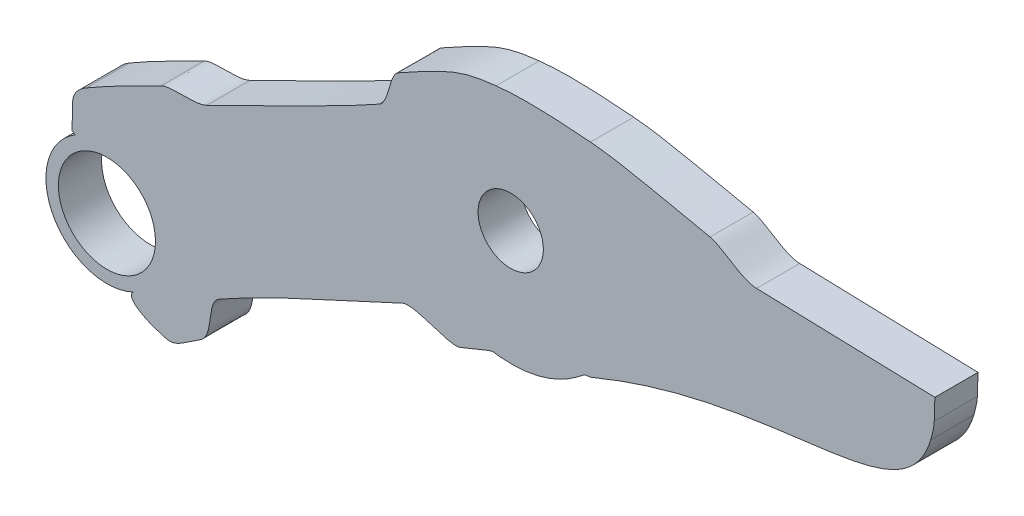
SolidWorks part; units mm, degrees
ref_plane "Front Plane" through (0, 0, 0) normal (0, 0, 1) x (1, 0, 0)
ref_plane "Top Plane" through (0, 0, 0) normal (0, 1, 0) x (1, 0, 0)
ref_plane "Right Plane" through (0, 0, 0) normal (1, 0, 0) x (0, 0, -1)
sketch "Sketch1" plane through (0, 0, 0) normal (0, 0, 1) x (1, 0, 0)
  line L0 (-137.3308, 84.7406) -> (-129.0656, 84.5002)
  line L1 (-129.0656, 84.5002) -> (-129.0945, 83.5194)
  line L2 (-163.1453, 69.7669) -> (-163.8803, 69.2822)
  line L3 (-168.9158, 75.1146) -> (-169.0656, 75.2055)
  line L4 (-169.0656, 75.2055) -> (-169.0647, 75.2443)
  line L5 (-169.0647, 75.2443) -> (-169.0372, 76.3501)
  circle A0 centre (-148.7285, 81.356) radius 1.5139
  circle A2 centre (-167.4471, 72.697) radius 2.25
  arc A3 (-168.9158, 75.1146) -> (-166.2168, 70.1499) centre (-167.4471, 72.697) ccw
  spline S0 degree 3 poles (-168.4092, 77.2502) (-167.0165, 78.0714) (-166.1939, 78.4009) (-164.9342, 79.0733) knots 0 0 0 0 0.021277 0.021277 0.021277 0.021277
  spline S1 degree 3 poles (-164.9342, 79.0733) (-164.5081, 79.3007) (-163.4053, 79.0621) (-162.8163, 79.3497) knots 0.021277 0.021277 0.021277 0.021277 0.042553 0.042553 0.042553 0.042553
  spline S2 degree 3 poles (-162.8163, 79.3497) (-160.7623, 80.3524) (-156.1822, 82.6064) (-154.8138, 83.3977) knots 0.042553 0.042553 0.042553 0.042553 0.06383 0.06383 0.06383 0.06383
  spline S3 degree 3 poles (-154.8138, 83.3977) (-154.3625, 83.6587) (-154.3604, 84.8581) (-153.9554, 85.0824) knots 0.06383 0.06383 0.06383 0.06383 0.085106 0.085106 0.085106 0.085106
  spline S4 degree 3 poles (-153.9554, 85.0824) (-151.5821, 86.3965) (-151.0528, 86.6559) (-149.4064, 86.8357) knots 0.085106 0.085106 0.085106 0.085106 0.106383 0.106383 0.106383 0.106383
  spline S5 degree 3 poles (-149.4064, 86.8357) (-148.2413, 86.963) (-146.873, 86.9196) (-145.0282, 86.7658) knots 0.106383 0.106383 0.106383 0.106383 0.12766 0.12766 0.12766 0.12766
  spline S6 degree 3 poles (-145.0282, 86.7658) (-143.5678, 86.644) (-141.7599, 86.1866) (-139.4864, 85.7276) knots 0.12766 0.12766 0.12766 0.12766 0.148936 0.148936 0.148936 0.148936
  spline S7 degree 3 poles (-139.4864, 85.7276) (-138.9479, 85.6189) (-138.0584, 84.7618) (-137.3308, 84.7406) knots 0.148936 0.148936 0.148936 0.148936 0.170213 0.170213 0.170213 0.170213
  spline S8 degree 3 poles (-129.0945, 83.5194) (-129.1011, 83.2912) (-129.1999, 82.8846) (-129.2593, 82.6893) knots 0.212766 0.212766 0.212766 0.212766 0.234043 0.234043 0.234043 0.234043
  spline S9 degree 3 poles (-129.2593, 82.6893) (-130.5236, 78.537) (-136.2953, 80.9813) (-144.9884, 77.341) knots 0.234043 0.234043 0.234043 0.234043 0.255319 0.255319 0.255319 0.255319
  spline S10 degree 3 poles (-144.9884, 77.341) (-145.098, 77.2951) (-145.0475, 77.3316) (-145.1632, 77.3099) knots 0.255319 0.255319 0.255319 0.255319 0.276596 0.276596 0.276596 0.276596
  spline S11 degree 3 poles (-145.1632, 77.3099) (-145.2207, 77.299) (-145.2859, 77.3027) (-145.3306, 77.2674) knots 0.276596 0.276596 0.276596 0.276596 0.297872 0.297872 0.297872 0.297872
  spline S12 degree 3 poles (-145.3306, 77.2674) (-145.8517, 76.8544) (-147.0892, 75.8481) (-149.2505, 76.0477) knots 0.297872 0.297872 0.297872 0.297872 0.319149 0.319149 0.319149 0.319149
  spline S13 degree 3 poles (-149.2505, 76.0477) (-149.5792, 76.078) (-149.4632, 76.1451) (-149.8232, 76.0078) knots 0.319149 0.319149 0.319149 0.319149 0.340426 0.340426 0.340426 0.340426
  spline S14 degree 3 poles (-149.8232, 76.0078) (-150.231, 75.8523) (-150.6422, 75.685) (-151.0603, 75.5052) knots 0.340426 0.340426 0.340426 0.340426 0.361702 0.361702 0.361702 0.361702
  spline S15 degree 3 poles (-151.0603, 75.5052) (-151.5746, 75.284) (-153.2037, 76.198) (-153.7457, 75.9373) knots 0.361702 0.361702 0.361702 0.361702 0.382979 0.382979 0.382979 0.382979
  spline S16 degree 3 poles (-153.7457, 75.9373) (-155.5948, 75.0478) (-159.7166, 73.2883) (-162.2325, 71.8588) knots 0.382979 0.382979 0.382979 0.382979 0.404255 0.404255 0.404255 0.404255
  spline S17 degree 3 poles (-162.2325, 71.8588) (-162.8608, 71.5018) (-162.4626, 70.2871) (-163.0718, 69.816) knots 0.404255 0.404255 0.404255 0.404255 0.425532 0.425532 0.425532 0.425532
  spline S18 degree 3 poles (-163.0718, 69.816) (-163.0947, 69.7983) (-163.1203, 69.7834) (-163.1453, 69.7669) knots 0.425532 0.425532 0.425532 0.425532 0.446809 0.446809 0.446809 0.446809
  spline S19 degree 3 poles (-163.8803, 69.2822) (-164.4683, 68.8945) (-164.6208, 69.006) (-165.1958, 69.1927) knots 0.468085 0.468085 0.468085 0.468085 0.489362 0.489362 0.489362 0.489362
  spline S20 degree 3 poles (-165.1958, 69.1927) (-165.8803, 69.4149) (-166.5866, 69.8768) (-166.2168, 70.1499) knots 0.489362 0.489362 0.489362 0.489362 0.509557 0.509557 0.509557 0.509557
  spline S39 degree 3 poles (-169.0372, 76.3501) (-169.0331, 76.794) (-168.7001, 77.0787) (-168.4092, 77.2502) knots 0.957447 0.957447 0.957447 0.957447 1 1 1 1
  dimension "D2" = 4.5
  dimension "D1" = 40
extrude "Boss-Extrude1" add sketch "Sketch1" along normal blind 2
scale "Scale1" scale about centroid uniform scaling yes scale factor 2.8
